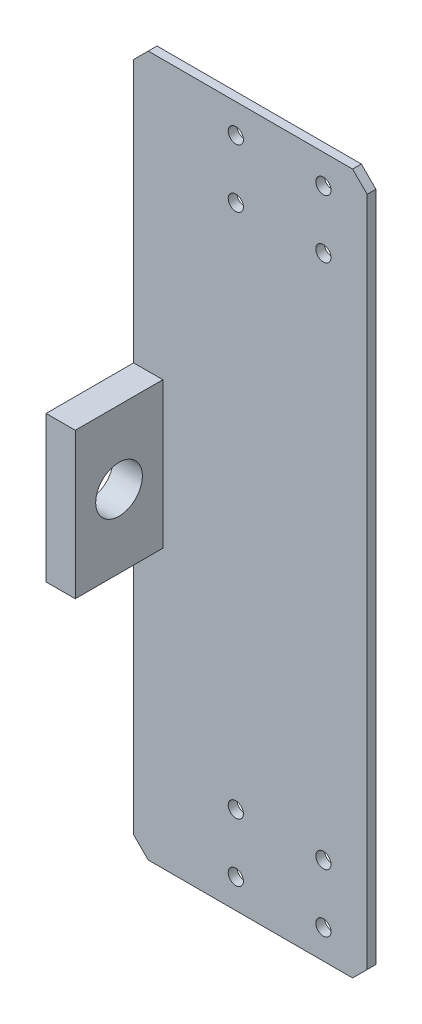
SolidWorks part; units mm, degrees
ref_plane "前视基准面" through (0, 0, 0) normal (0, 0, 1) x (1, 0, 0)
ref_plane "上视基准面" through (0, 0, 0) normal (0, 1, 0) x (1, 0, 0)
ref_plane "右视基准面" through (0, 0, 0) normal (1, 0, 0) x (0, 0, -1)
other "Configuration Table"
sketch "草图1" plane through (0, 0, 0) normal (0, 0, 1) x (1, 0, 0)
  line L0 (0, 0) -> (177289.5009, 0) construction
  line L1 (195, 115) -> (190, 115)
  line L2 (190, 115) -> (190, 120)
  line L3 (0, 0) -> (0, 177289.5009) construction
  line L4 (-175, 120) -> (-175, 90)
  line L5 (-195, 120) -> (195, 120)
  line L6 (-195, 120) -> (-195, -120)
  line L7 (-195, -120) -> (195, -120)
  line L8 (195, 120) -> (195, -120)
  line L9 (-45, 60) -> (45, 60)
  line L10 (-45, 60) -> (-45, -60)
  line L11 (-45, -60) -> (45, -60)
  line L12 (45, 60) -> (45, -60)
  line L13 (-175, 90) -> (-195, 90)
  line L14 (-175, 120) -> (-195, 90)
  line L15 (-175, 120) -> (-130, 120)
  line L16 (190, 120) -> (195, 115)
  line L17 (190, 120) -> (115, 120)
  line L18 (115, 120) -> (115, 75)
  line L19 (115, 75) -> (75, 75)
  line L20 (-130, 120) -> (-130, 75)
  line L21 (-130, 75) -> (-90, 75)
  line L22 (-130, 120) -> (-90, 75)
  line L23 (115, 120) -> (75, 75)
  line L24 (-90, 75) -> (75, 75)
  line L25 (-130, 120) -> (115, 120)
  line L26 (190, -115) -> (190, -120)
  line L27 (195, -115) -> (190, -115)
  line L28 (190, -120) -> (195, -115)
  line L29 (-90, -75) -> (75, -75)
  line L30 (115, -120) -> (115, -75)
  line L31 (115, -75) -> (75, -75)
  line L32 (115, -120) -> (75, -75)
  line L33 (-130, -120) -> (-130, -75)
  line L34 (-130, -75) -> (-90, -75)
  line L35 (-130, -120) -> (-90, -75)
  line L36 (-175, -120) -> (-175, -90)
  line L37 (-175, -90) -> (-195, -90)
  line L38 (-175, -120) -> (-195, -90)
  circle A0 centre (-184.0895, 70) radius 3
  circle A1 centre (104.3795, 93) radius 3
  circle A2 centre (75, 0) radius 10
  circle A3 centre (117.5, 0) radius 7.5
  circle A4 centre (104.3795, -93) radius 3
  circle A5 centre (-184.0895, -70) radius 3
  circle A7 centre (-87, 69) radius 3
  circle A8 centre (-87, -69) radius 3
  point P4 (0, 0)
  point P46 (45, 0)
  dimension "D16" = 6
  dimension "D17" = 6
  dimension "D20" = 20
  dimension "D21" = 30
  dimension "D22" = 42.5
  dimension "D23" = 15
  dimension "D25" = 6
  dimension "D1" = 240
  dimension "D2" = 390
  dimension "D3" = 90
  dimension "D4" = 120
  dimension "D5" = 30
  dimension "D6" = 20
  dimension "D7" = 45
  dimension "D8" = 5
  dimension "D9" = 5
  dimension "D10" = 75
  dimension "D11" = 45
  dimension "D12" = 40
  dimension "D13" = 45
  dimension "D14" = 40
  dimension "D15" = 20
  dimension "D18" = 27
  dimension "D19" = 10
  dimension "D24" = 3
  dimension "D26" = 6
extrude "凸台-拉伸2" add sketch "草图1" along normal blind 3 contours L37 L36 L7 L33 L34 L29 L31 L30 L26 L27 L8 L1 L2 L5 L18 L19 L24 L21 L20 L4 L13 L6 A5 A3 A2 A0 L9 L12 L11 L10 A7 A8 | L22 L20 L21 | L4 L14 L13 | L38 L36 L37 | L33 L35 L34 | L32 L30 L31 A4 | L18 L23 L19 A1 | L16 L2 L1 | L26 L28 L27
sketch "草图2" plane through (0, 0, 3) normal (0, 0, 1) x (1, 0, 0)
  circle A0 centre (75, 0) radius 10
  circle A1 centre (117.5, 0) radius 7.5
extrude "凸台-拉伸3" add sketch "草图2" against normal blind 3
sketch "草图3" plane through (0, 0, 3) normal (0, 0, 1) x (1, 0, 0)
  line L0 (115, 120) -> (115, -120)
  line L1 (115, -115) -> (120, -115)
  line L2 (115, 120) -> (190, 120) construction
  line L3 (115, -120) -> (190, -120) construction
  line L4 (195, 115) -> (195, -115) construction
  line L5 (120, 120) -> (120, 115)
  line L6 (120, 115) -> (115, 115)
  line L7 (115, 115) -> (120, 120)
  line L8 (120, -115) -> (120, -120)
  line L9 (120, -120) -> (115, -115)
  line M6 (-195, 90) -> (-195, -90)
  line M7 (-195, -90) -> (-175, -120)
  line M8 (-175, -120) -> (-130, -120)
  line M9 (-130, -120) -> (-90, -75)
  line M10 (-90, -75) -> (75, -75)
  line M11 (75, -75) -> (115, -120)
  line M12 (115, -120) -> (190, -120)
  line M16 (190, 120) -> (115, 120)
  line M17 (115, 120) -> (75, 75)
  line M18 (75, 75) -> (-90, 75)
  line M19 (-90, 75) -> (-130, 120)
  line M20 (-130, 120) -> (-175, 120)
  line M21 (-175, 120) -> (-195, 90)
  circle M22 centre (-184.0895, -70) radius 3
  circle M23 centre (-184.0895, 70) radius 3
  line M24 (-45, 60) -> (45, 60)
  line M25 (45, 60) -> (45, -60)
  line M26 (45, -60) -> (-45, -60)
  line M27 (-45, -60) -> (-45, 60)
  circle M28 centre (-87, 69) radius 3
  circle M29 centre (-87, -69) radius 3
  circle M30 centre (104.3795, 93) radius 3
  circle M31 centre (104.3795, -93) radius 3
  dimension "D1" = 80
  dimension "D2" = 5
  dimension "D3" = 5
  dimension "D4" = 5
  dimension "D5" = 5
extrude "切除-拉伸2" cut sketch "草图3" against normal blind 3 contours L0 M17 M18 M19 M20 M21 M6 M7 M8 M9 M10 M11 M22 M27 M24 M25 M26 M28 M30 M31 M29 M23 | L9 L0 M12 | L0 L7 M16
sketch "草图4" plane through (0, 0, 3) normal (0, 0, 1) x (1, 0, 0)
  line L0 (115, 0) -> (50115, 0) construction
  line L1 (115, 115) -> (115, -115) construction
  line L2 (155, -120) -> (155, 49880) construction
  line L3 (120, -120) -> (190, -120) construction
  line L5 (115, 25) -> (125, 25)
  line L6 (115, 25) -> (115, -25)
  line L7 (115, -25) -> (125, -25)
  line L8 (125, 25) -> (125, -25)
  point P4 (115, 0)
  point P9 (155, -120)
  dimension "D1" = 10
  dimension "D2" = 50
extrude "凸台-拉伸4" add sketch "草图4" along normal blind 30 contours L6 L5 L8 L7
sketch "草图5" plane through (115, 0, 0) normal (-1, 0, 0) x (0, 0, 1)
  line L0 (0, 0) -> (50000, 0) construction
  line L1 (18, -25) -> (18, 49975) construction
  line L2 (33, -25) -> (3, -25) construction
  circle A0 centre (18, 0) radius 8
  point P7 (18, -25)
extrude "切除-拉伸3" cut sketch "草图5" against normal blind 30
sketch "草图6" plane through (0, 0, 3) normal (0, 0, 1) x (1, 0, 0)
  line L0 (155, 120) -> (155, 50120) construction
  line L1 (120, 120) -> (190, 120) construction
  line L2 (195, 0) -> (50195, 0) construction
  line L3 (195, 115) -> (195, -115) construction
  line L4 (185, -120) -> (185, -80)
  line L5 (120, -120) -> (190, -120) construction
  line L6 (185, -80) -> (145, -80)
  line L7 (145, -80) -> (145, -120)
  line L8 (165, -80) -> (165, 49920) construction
  line L9 (155, -100) -> (50155, -100) construction
  circle A0 centre (180, -90) radius 2.6
  circle A1 centre (150, -90) radius 2.6
  circle A2 centre (150, -110) radius 2.6
  circle A3 centre (180, -110) radius 2.6
  circle A4 centre (150, 110) radius 2.6
  circle A5 centre (180, 110) radius 2.6
  circle A6 centre (180, 90) radius 2.6
  circle A7 centre (150, 90) radius 2.6
  point P4 (155, 120)
  point P9 (195, 0)
  point P19 (165, -80)
  point P22 (145, -100)
  dimension "D4" = 10
  dimension "D1" = 5
  dimension "D2" = 40
  dimension "D3" = 40
  dimension "D5" = 30
extrude "切除-拉伸5" cut sketch "草图6" against normal blind 10 contours A7 | A6 | A5 | A4 | A1 | A2 | A3 | A0
